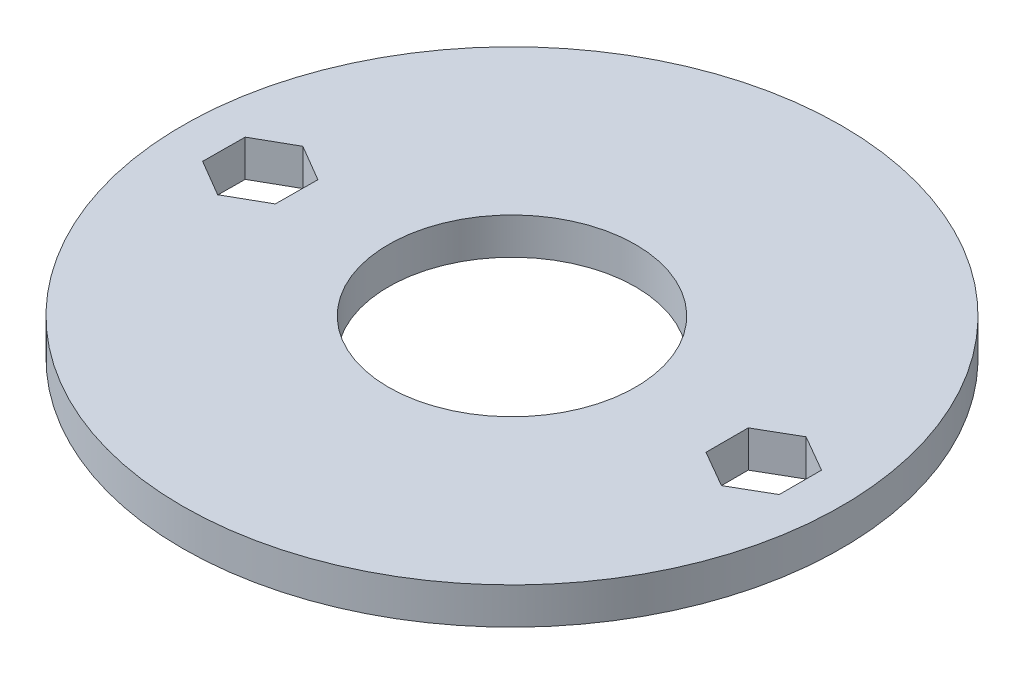
SolidWorks part; units mm, degrees
ref_plane "Front Plane" through (0, 0, 0) normal (0, 0, 1) x (1, 0, 0)
ref_plane "Top Plane" through (0, 0, 0) normal (0, 1, 0) x (1, 0, 0)
ref_plane "Right Plane" through (0, 0, 0) normal (1, 0, 0) x (0, 0, -1)
sketch "Sketch1" plane through (0, 0, 0) normal (0, 1, 0) x (1, 0, 0)
  circle A0 centre (0, 0) radius 36
  dimension "D1" = 72
extrude "Boss-Extrude1" add sketch "Sketch1" along normal blind 4
sketch "Sketch2" plane through (0, 4, 0) normal (0, 1, 0) x (1, 0, 0)
  line L0 (-36, 0) -> (36, 0) construction
  line L1 (0, 36) -> (0, -36) construction
  line L3 (-31.5177, -2.2784) -> (-27.5357, -4.6187)
  line L4 (-27.5357, -4.6187) -> (-23.518, -2.3403)
  line L5 (-23.518, -2.3403) -> (-23.4823, 2.2784)
  line L6 (-23.4823, 2.2784) -> (-27.4643, 4.6187)
  line L7 (-27.4643, 4.6187) -> (-31.482, 2.3403)
  line L8 (-31.482, 2.3403) -> (-31.5177, -2.2784)
  line L9 (27.5, -4.6188) -> (31.5, -2.3094)
  line L10 (31.5, -2.3094) -> (31.5, 2.3094)
  line L11 (31.5, 2.3094) -> (27.5, 4.6188)
  line L12 (27.5, 4.6188) -> (23.5, 2.3094)
  line L13 (23.5, 2.3094) -> (23.5, -2.3094)
  line L14 (23.5, -2.3094) -> (27.5, -4.6188)
  circle A0 centre (0, 0) radius 36 construction
  circle A3 centre (-27.5, 0) radius 4 construction
  circle A4 centre (27.5, 0) radius 4 construction
  dimension "D2" = 55
  dimension "D3" = 8
  dimension "D4" = 8
extrude "Cut-Extrude1" cut sketch "Sketch2" against normal through all
sketch "Sketch3" plane through (0, 4, 0) normal (0, 1, 0) x (1, 0, 0)
  circle A0 centre (0, 0) radius 13.5
  dimension "D1" = 27
extrude "Cut-Extrude2" cut sketch "Sketch3" against normal through all
